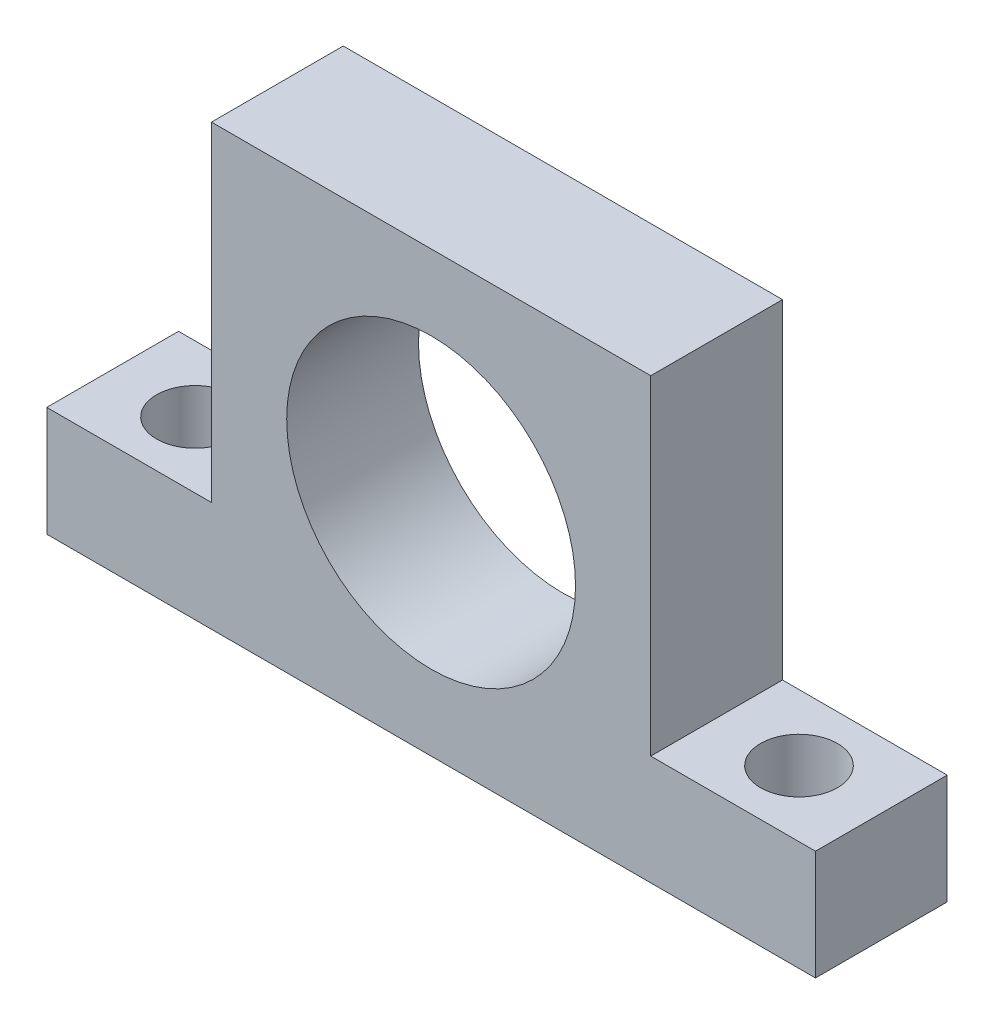
SolidWorks part; units mm, degrees
ref_plane "前基準面" through (0, 0, 0) normal (0, 0, 1) x (1, 0, 0)
ref_plane "上基準面" through (0, 0, 0) normal (0, 1, 0) x (1, 0, 0)
ref_plane "右基準面" through (0, 0, 0) normal (1, 0, 0) x (0, 0, -1)
sketch "草圖1" plane through (0, 0, 0) normal (0, 0, 1) x (1, 0, 0)
  line L0 (40, 0) -> (55, 0)
  line L2 (0, 0) -> (0, 30)
  line L3 (0, 30) -> (40, 30)
  line L4 (40, 0) -> (40, 30)
  line L5 (-15, 0) -> (0, 0)
  line L6 (-15, 0) -> (-15, -10)
  line L7 (-15, -10) -> (55, -10)
  line L8 (55, 0) -> (55, -10)
  circle A0 centre (20, 10) radius 13.15
  point P11 (20, 30)
  point P12 (20, -10)
  dimension "D1" = 26.3
  dimension "D2" = 20
  dimension "D3" = 10
  dimension "D4" = 30
  dimension "D5" = 40
  dimension "D6" = 15
extrude "填料-伸長1" add sketch "草圖1" along normal blind 12 contours A0 | L2 L3 L4 L0 L8 L7 L6 L5
sketch "草圖2" plane through (0, 0, 0) normal (0, 1, 0) x (1, 0, 0)
  line L0 (40, -12) -> (55, -12) construction
  line L1 (55, -12) -> (55, 0) construction
  circle A0 centre (47.5, -6) radius 3.5
  point P5 (47.5, -12)
  point P9 (55, -6)
  dimension "D1" = 7
extrude "除料-伸長2" cut sketch "草圖2" against normal through all contours A0
sketch "草圖3" plane through (0, 0, 0) normal (0, 1, 0) x (1, 0, 0)
  line L0 (-15, -12) -> (-15, 0) construction
  line L1 (-15, 0) -> (0, 0) construction
  circle A0 centre (-7.5, -6) radius 3.5
  point P5 (-15, -6)
  point P8 (-7.5, 0)
  dimension "D1" = 7
extrude "除料-伸長3" cut sketch "草圖3" against normal through all
